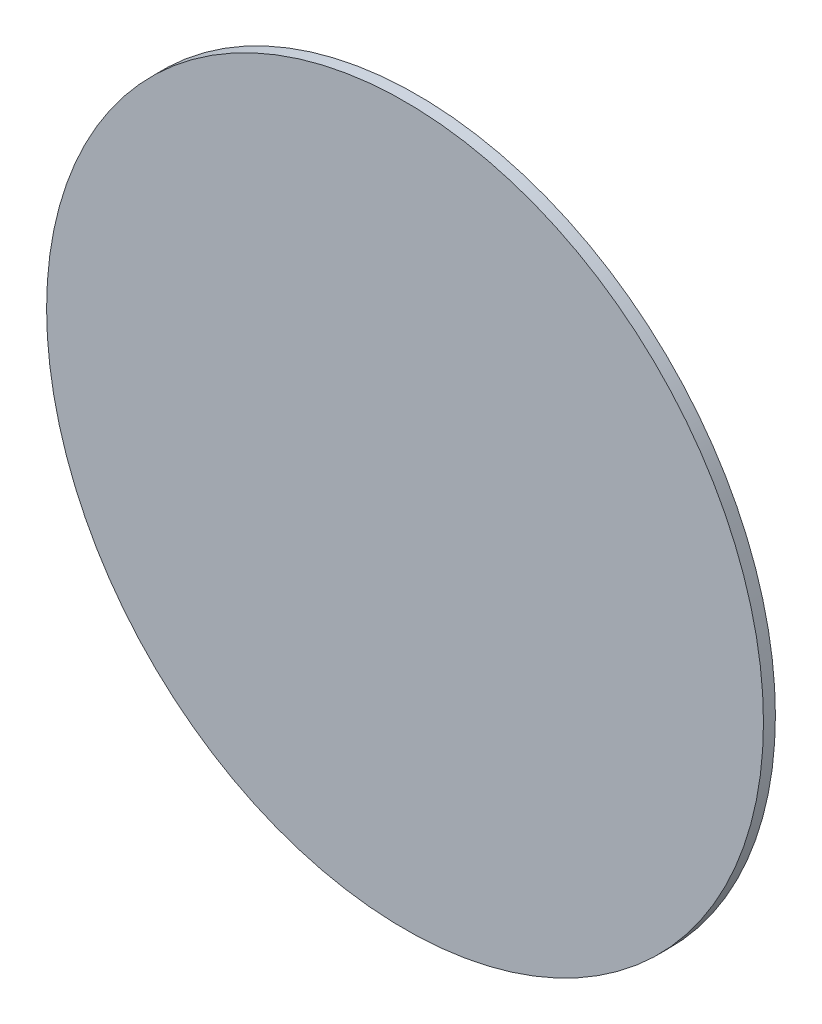
SolidWorks part; units mm, degrees
ref_plane "Front Plane" through (0, 0, 0) normal (0, 0, 1) x (1, 0, 0)
ref_plane "Top Plane" through (0, 0, 0) normal (0, 1, 0) x (1, 0, 0)
ref_plane "Right Plane" through (0, 0, 0) normal (1, 0, 0) x (0, 0, -1)
sketch "Sketch1" plane through (0, 0, 0) normal (0, 0, 1) x (1, 0, 0)
  circle A0 centre (-203.2643, 322.3024) radius 60
  dimension "D1" = 120
extrude "Boss-Extrude1" add sketch "Sketch1" along normal blind 2
